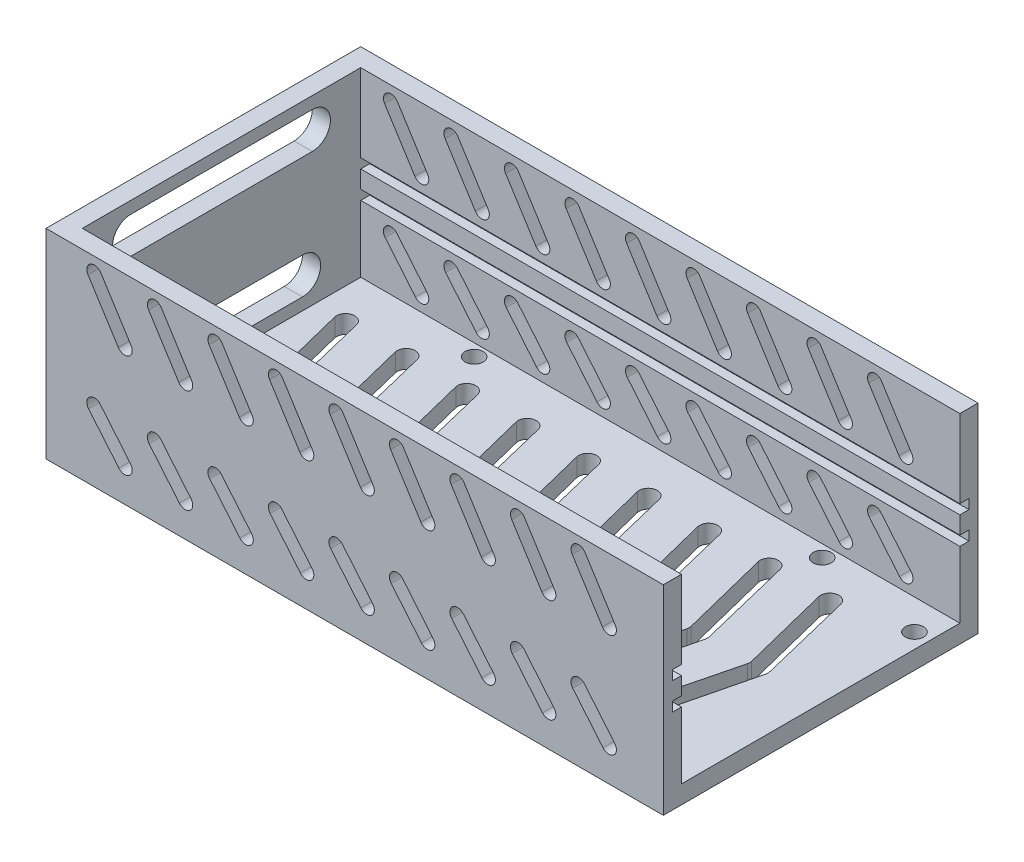
SolidWorks part; units mm, degrees
ref_plane "Front Plane" through (0, 0, 0) normal (0, 0, 1) x (1, 0, 0)
ref_plane "Top Plane" through (0, 0, 0) normal (0, 1, 0) x (1, 0, 0)
ref_plane "Right Plane" through (0, 0, 0) normal (1, 0, 0) x (0, 0, -1)
sketch "Sketch1" plane through (0, 0, 0) normal (0, 1, 0) x (1, 0, 0)
  line L0 (-28.75, 21) -> (28.75, 21) construction
  line L1 (-28.75, 21) -> (-28.75, -21) construction
  line L2 (-25.25, -21) -> (25.25, -21) construction
  line L3 (-49.5, -26) -> (49.5, -26)
  line L4 (-49.5, -26) -> (-49.5, 26)
  line L5 (-49.5, 26) -> (49.5, 26)
  line L6 (49.5, -26) -> (49.5, 26)
  line L7 (-49.5, -26) -> (49.5, 26) construction
  line L8 (-49.5, 26) -> (49.5, -26) construction
  circle A0 centre (28.75, 21) radius 1.5
  circle A1 centre (-28.75, 21) radius 1.5
  circle A2 centre (25.25, -21) radius 1.5
  circle A3 centre (-25.25, -21) radius 1.5
  point P8 (0, 21)
  point P10 (-28.75, 0)
  point P11 (0, 0)
  point P17 (0, -21)
  dimension "D1" = 3
  dimension "D2" = 3
  dimension "D3" = 3
  dimension "D4" = 3
  dimension "D5" = 57.5
  dimension "D6" = 50.5
  dimension "D7" = 42
  dimension "D8" = 42
  dimension "D9" = 52
  dimension "D10" = 99
extrude "Boss-Extrude1" add sketch "Sketch1" along normal blind 33
sketch "Sketch2" plane through (0, 33, 0) normal (0, 1, 0) x (1, 0, 0)
  line L5 (49.5, -26) -> (49.5, 26) construction
  line L6 (-49.5, -23) -> (49.5, -23)
  line L8 (-49.5, -23) -> (-49.5, 23)
  line L9 (-49.5, 23) -> (49.5, 23)
  line L10 (49.5, -23) -> (49.5, 23)
  line L11 (-49.5, -23) -> (49.5, 23) construction
  line L12 (-49.5, 23) -> (49.5, -23) construction
  point P0 (0, 0)
  dimension "D1" = 46
extrude "Cut-Extrude1" cut sketch "Sketch2" against normal blind 30
sketch "Sketch3" plane through (49.5, 0, 0) normal (1, 0, 0) x (0, 0, -1)
  line L0 (-23, 3) -> (-23, 33) construction
  line L1 (-23, 15.6) -> (-24.5, 15.6)
  line L2 (-23, 15.6) -> (-23, 14)
  line L3 (-23, 14) -> (-24.5, 14)
  line L4 (-24.5, 15.6) -> (-24.5, 14)
  line L5 (-23, 3) -> (23, 3) construction
  line L6 (0, 0) -> (0, 22.1348) construction
  line L7 (24.5, 15.6) -> (24.5, 14)
  line L8 (23, 14) -> (24.5, 14)
  line L9 (23, 15.6) -> (23, 14)
  line L10 (23, 15.6) -> (24.5, 15.6)
  line L11 (-23, 18.5) -> (-24.5, 18.5)
  line L12 (-24.5, 20.1) -> (-24.5, 18.5)
  line L13 (-23, 20.1) -> (-23, 18.5)
  line L14 (-23, 20.1) -> (-24.5, 20.1)
  line L15 (23, 20.1) -> (24.5, 20.1)
  line L16 (23, 20.1) -> (23, 18.5)
  line L17 (24.5, 20.1) -> (24.5, 18.5)
  line L18 (23, 18.5) -> (24.5, 18.5)
  point P19 (-23.75, 18.5)
  point P20 (-23.75, 15.6)
  dimension "D1" = 1.5
  dimension "D2" = 1.6
  dimension "D3" = 11
  dimension "D4" = 2.9
  dimension "D5" = 1.5
  dimension "D6" = 1.6
extrude "Cut-Extrude2" cut sketch "Sketch3" against normal up to surface (99 mm away) up to face at (-49.5, 17.25, 0)
sketch "Sketch4" plane through (0, 0, 0) normal (0, 1, 0) x (1, 0, 0)
  line L1 (-49.5, 26) -> (-52.5, 26)
  line L2 (-49.5, 26) -> (-49.5, -26)
  line L3 (-49.5, -26) -> (-52.5, -26)
  line L4 (-52.5, 26) -> (-52.5, -26)
  dimension "D1" = 52
  dimension "D2" = 3
extrude "Boss-Extrude2" add sketch "Sketch4" along normal up to surface (33 mm away) up to face at (0, 33, -24.5)
sketch "Sketch5" plane through (-49.5, 0, 0) normal (1, 0, 0) x (0, 0, -1)
  line L0 (-15, 31) -> (15, 31)
  line L1 (-15, 25) -> (15, 25)
  line L4 (-13.3752, 11) -> (13.3752, 11)
  line L5 (-13.3752, 5) -> (13.3752, 5)
  line L7 (23, 3) -> (-23, 3) construction
  line L8 (23, 33) -> (-23, 33) construction
  arc A0 (15, 25) -> (15, 31) centre (15, 28) ccw
  arc A1 (-15, 31) -> (-15, 25) centre (-15, 28) ccw
  arc A2 (-13.3752, 11) -> (-13.3752, 5) centre (-13.3752, 8) ccw
  arc A3 (13.3752, 5) -> (13.3752, 11) centre (13.3752, 8) ccw
  point P3 (0, 31)
  dimension "D1" = 6
  dimension "D2" = 6
  dimension "D3" = 6
  dimension "D4" = 6
  dimension "D5" = 2
  dimension "D6" = 2
  dimension "D7" = 30
extrude "Cut-Extrude3" cut sketch "Sketch5" against normal up to surface (3 mm away) up to face at (-52.5, 16.5, 0)
sketch "Sketch6" plane through (0, 0, -23) normal (0, 0, 1) x (1, 0, 0)
  line L0 (-45.5562, 29.8315) -> (-40.5562, 21.9315)
  line L1 (-44.5, 30.5) -> (-39.5, 22.6) construction
  line L2 (-43.4438, 31.1685) -> (-38.4438, 23.2685)
  line L3 (49.5, 33) -> (-49.5, 33) construction
  line L4 (-49.5, 20.1) -> (49.5, 20.1) construction
  line L5 (-49.5, 20.1) -> (-49.5, 33) construction
  line L6 (-43.5397, 12.3002) -> (-38.5397, 6.3002)
  line L7 (-44.5, 11.5) -> (-39.5, 5.5) construction
  line L8 (-45.4603, 10.6998) -> (-40.4603, 4.6998)
  line L9 (-49.5, 3) -> (-49.5, 14) construction
  line L10 (-49.5, 14) -> (49.5, 14) construction
  line L11 (49.5, 3) -> (-49.5, 3) construction
  line L12 (-35.5562, 29.8315) -> (-30.5562, 21.9315)
  line L13 (-33.4438, 31.1685) -> (-28.4438, 23.2685)
  line L14 (-33.5397, 12.3002) -> (-28.5397, 6.3002)
  line L15 (-35.4603, 10.6998) -> (-30.4603, 4.6998)
  line L16 (-34.5, 30.5) -> (-29.5, 22.6) construction
  line L17 (-34.5, 11.5) -> (-29.5, 5.5) construction
  line L18 (-25.5562, 29.8315) -> (-20.5562, 21.9315)
  line L19 (-23.4438, 31.1685) -> (-18.4438, 23.2685)
  line L20 (-23.5397, 12.3002) -> (-18.5397, 6.3002)
  line L21 (-25.4603, 10.6998) -> (-20.4603, 4.6998)
  line L22 (-24.5, 30.5) -> (-19.5, 22.6) construction
  line L23 (-24.5, 11.5) -> (-19.5, 5.5) construction
  line L24 (-15.5562, 29.8315) -> (-10.5562, 21.9315)
  line L25 (-13.4438, 31.1685) -> (-8.4438, 23.2685)
  line L26 (-13.5397, 12.3002) -> (-8.5397, 6.3002)
  line L27 (-15.4603, 10.6998) -> (-10.4603, 4.6998)
  line L28 (-14.5, 30.5) -> (-9.5, 22.6) construction
  line L29 (-14.5, 11.5) -> (-9.5, 5.5) construction
  line L30 (-5.5562, 29.8315) -> (-0.5562, 21.9315)
  line L31 (-3.4438, 31.1685) -> (1.5562, 23.2685)
  line L32 (-3.5397, 12.3002) -> (1.4603, 6.3002)
  line L33 (-5.4603, 10.6998) -> (-0.4603, 4.6998)
  line L34 (-4.5, 30.5) -> (0.5, 22.6) construction
  line L35 (-4.5, 11.5) -> (0.5, 5.5) construction
  line L36 (4.4438, 29.8315) -> (9.4438, 21.9315)
  line L37 (6.5562, 31.1685) -> (11.5562, 23.2685)
  line L38 (6.4603, 12.3002) -> (11.4603, 6.3002)
  line L39 (4.5397, 10.6998) -> (9.5397, 4.6998)
  line L40 (5.5, 30.5) -> (10.5, 22.6) construction
  line L41 (5.5, 11.5) -> (10.5, 5.5) construction
  line L42 (14.4438, 29.8315) -> (19.4438, 21.9315)
  line L43 (16.5562, 31.1685) -> (21.5562, 23.2685)
  line L44 (16.4603, 12.3002) -> (21.4603, 6.3002)
  line L45 (14.5397, 10.6998) -> (19.5397, 4.6998)
  line L46 (15.5, 30.5) -> (20.5, 22.6) construction
  line L47 (15.5, 11.5) -> (20.5, 5.5) construction
  line L48 (24.4438, 29.8315) -> (29.4438, 21.9315)
  line L49 (26.5562, 31.1685) -> (31.5562, 23.2685)
  line L50 (26.4603, 12.3002) -> (31.4603, 6.3002)
  line L51 (24.5397, 10.6998) -> (29.5397, 4.6998)
  line L52 (25.5, 30.5) -> (30.5, 22.6) construction
  line L53 (25.5, 11.5) -> (30.5, 5.5) construction
  line L54 (34.4438, 29.8315) -> (39.4438, 21.9315)
  line L55 (36.5562, 31.1685) -> (41.5562, 23.2685)
  line L56 (36.4603, 12.3002) -> (41.4603, 6.3002)
  line L57 (34.5397, 10.6998) -> (39.5397, 4.6998)
  line L58 (35.5, 30.5) -> (40.5, 22.6) construction
  line L59 (35.5, 11.5) -> (40.5, 5.5) construction
  arc A0 (-43.4438, 31.1685) -> (-45.5562, 29.8315) centre (-44.5, 30.5) ccw
  arc A1 (-40.5562, 21.9315) -> (-38.4438, 23.2685) centre (-39.5, 22.6) ccw
  arc A2 (-40.4603, 4.6998) -> (-38.5397, 6.3002) centre (-39.5, 5.5) ccw
  arc A3 (-43.5397, 12.3002) -> (-45.4603, 10.6998) centre (-44.5, 11.5) ccw
  arc A4 (-33.4438, 31.1685) -> (-35.5562, 29.8315) centre (-34.5, 30.5) ccw
  arc A5 (-30.5562, 21.9315) -> (-28.4438, 23.2685) centre (-29.5, 22.6) ccw
  arc A6 (-30.4603, 4.6998) -> (-28.5397, 6.3002) centre (-29.5, 5.5) ccw
  arc A7 (-33.5397, 12.3002) -> (-35.4603, 10.6998) centre (-34.5, 11.5) ccw
  arc A8 (-23.4438, 31.1685) -> (-25.5562, 29.8315) centre (-24.5, 30.5) ccw
  arc A9 (-20.5562, 21.9315) -> (-18.4438, 23.2685) centre (-19.5, 22.6) ccw
  arc A10 (-20.4603, 4.6998) -> (-18.5397, 6.3002) centre (-19.5, 5.5) ccw
  arc A11 (-23.5397, 12.3002) -> (-25.4603, 10.6998) centre (-24.5, 11.5) ccw
  arc A12 (-13.4438, 31.1685) -> (-15.5562, 29.8315) centre (-14.5, 30.5) ccw
  arc A13 (-10.5562, 21.9315) -> (-8.4438, 23.2685) centre (-9.5, 22.6) ccw
  arc A14 (-10.4603, 4.6998) -> (-8.5397, 6.3002) centre (-9.5, 5.5) ccw
  arc A15 (-13.5397, 12.3002) -> (-15.4603, 10.6998) centre (-14.5, 11.5) ccw
  arc A16 (-3.4438, 31.1685) -> (-5.5562, 29.8315) centre (-4.5, 30.5) ccw
  arc A17 (-0.5562, 21.9315) -> (1.5562, 23.2685) centre (0.5, 22.6) ccw
  arc A18 (-0.4603, 4.6998) -> (1.4603, 6.3002) centre (0.5, 5.5) ccw
  arc A19 (-3.5397, 12.3002) -> (-5.4603, 10.6998) centre (-4.5, 11.5) ccw
  arc A20 (6.5562, 31.1685) -> (4.4438, 29.8315) centre (5.5, 30.5) ccw
  arc A21 (9.4438, 21.9315) -> (11.5562, 23.2685) centre (10.5, 22.6) ccw
  arc A22 (9.5397, 4.6998) -> (11.4603, 6.3002) centre (10.5, 5.5) ccw
  arc A23 (6.4603, 12.3002) -> (4.5397, 10.6998) centre (5.5, 11.5) ccw
  arc A24 (16.5562, 31.1685) -> (14.4438, 29.8315) centre (15.5, 30.5) ccw
  arc A25 (19.4438, 21.9315) -> (21.5562, 23.2685) centre (20.5, 22.6) ccw
  arc A26 (19.5397, 4.6998) -> (21.4603, 6.3002) centre (20.5, 5.5) ccw
  arc A27 (16.4603, 12.3002) -> (14.5397, 10.6998) centre (15.5, 11.5) ccw
  arc A28 (26.5562, 31.1685) -> (24.4438, 29.8315) centre (25.5, 30.5) ccw
  arc A29 (29.4438, 21.9315) -> (31.5562, 23.2685) centre (30.5, 22.6) ccw
  arc A30 (29.5397, 4.6998) -> (31.4603, 6.3002) centre (30.5, 5.5) ccw
  arc A31 (26.4603, 12.3002) -> (24.5397, 10.6998) centre (25.5, 11.5) ccw
  arc A32 (36.5562, 31.1685) -> (34.4438, 29.8315) centre (35.5, 30.5) ccw
  arc A33 (39.4438, 21.9315) -> (41.5562, 23.2685) centre (40.5, 22.6) ccw
  arc A34 (39.5397, 4.6998) -> (41.4603, 6.3002) centre (40.5, 5.5) ccw
  arc A35 (36.4603, 12.3002) -> (34.5397, 10.6998) centre (35.5, 11.5) ccw
  dimension "D1" = 2.5
  dimension "D2" = 2.5
  dimension "D7" = 2.5
  dimension "D8" = 2.5
  dimension "D3" = 2.5
  dimension "D4" = 2.5
  dimension "D5" = 5
  dimension "D6" = 5
  dimension "D9" = 5
  dimension "D10" = 5
  dimension "D11" = 2.5
  dimension "D12" = 2.5
  dimension "D13" = 9
extrude "Cut-Extrude4" cut sketch "Sketch6" against normal up to surface (3 mm away) up to face at (-1.5, 16.5, -26)
sketch "Sketch7" plane through (0, 0, -26) normal (0, 0, -1) x (-1, 0, 0)
  line L0 (40.5562, 21.9315) -> (45.5562, 29.8315)
  line L1 (43.4438, 31.1685) -> (38.4438, 23.2685)
  line L2 (43.5397, 12.3002) -> (38.5397, 6.3002)
  line L3 (40.4603, 4.6998) -> (45.4603, 10.6998)
  line L4 (30.5562, 21.9315) -> (35.5562, 29.8315)
  line L5 (33.4438, 31.1685) -> (28.4438, 23.2685)
  line L6 (33.5397, 12.3002) -> (28.5397, 6.3002)
  line L7 (30.4603, 4.6998) -> (35.4603, 10.6998)
  line L8 (20.5562, 21.9315) -> (25.5562, 29.8315)
  line L9 (23.4438, 31.1685) -> (18.4438, 23.2685)
  line L10 (23.5397, 12.3002) -> (18.5397, 6.3002)
  line L11 (20.4603, 4.6998) -> (25.4603, 10.6998)
  line L12 (10.5562, 21.9315) -> (15.5562, 29.8315)
  line L13 (13.4438, 31.1685) -> (8.4438, 23.2685)
  line L14 (13.5397, 12.3002) -> (8.5397, 6.3002)
  line L15 (10.4603, 4.6998) -> (15.4603, 10.6998)
  line L16 (0.5562, 21.9315) -> (5.5562, 29.8315)
  line L17 (3.4438, 31.1685) -> (-1.5562, 23.2685)
  line L18 (3.5397, 12.3002) -> (-1.4603, 6.3002)
  line L19 (0.4603, 4.6998) -> (5.4603, 10.6998)
  line L20 (-9.4438, 21.9315) -> (-4.4438, 29.8315)
  line L21 (-6.5562, 31.1685) -> (-11.5562, 23.2685)
  line L22 (-6.4603, 12.3002) -> (-11.4603, 6.3002)
  line L23 (-9.5397, 4.6998) -> (-4.5397, 10.6998)
  line L24 (-19.4438, 21.9315) -> (-14.4438, 29.8315)
  line L25 (-16.5562, 31.1685) -> (-21.5562, 23.2685)
  line L26 (-16.4603, 12.3002) -> (-21.4603, 6.3002)
  line L27 (-19.5397, 4.6998) -> (-14.5397, 10.6998)
  line L28 (-29.4438, 21.9315) -> (-24.4438, 29.8315)
  line L29 (-26.5562, 31.1685) -> (-31.5562, 23.2685)
  line L30 (-26.4603, 12.3002) -> (-31.4603, 6.3002)
  line L31 (-29.5397, 4.6998) -> (-24.5397, 10.6998)
  line L32 (-39.4438, 21.9315) -> (-34.4438, 29.8315)
  line L33 (-36.5562, 31.1685) -> (-41.5562, 23.2685)
  line L34 (-36.4603, 12.3002) -> (-41.4603, 6.3002)
  line L35 (-39.5397, 4.6998) -> (-34.5397, 10.6998)
  arc A0 (45.5562, 29.8315) -> (43.4438, 31.1685) centre (44.5, 30.5) ccw
  arc A1 (38.4438, 23.2685) -> (40.5562, 21.9315) centre (39.5, 22.6) ccw
  arc A2 (38.5397, 6.3002) -> (40.4603, 4.6998) centre (39.5, 5.5) ccw
  arc A3 (45.4603, 10.6998) -> (43.5397, 12.3002) centre (44.5, 11.5) ccw
  arc A4 (45.4603, 10.6998) -> (43.5397, 12.3002) centre (44.5, 11.5) ccw construction
  arc A5 (38.5397, 6.3002) -> (40.4603, 4.6998) centre (39.5, 5.5) ccw construction
  arc A6 (35.5562, 29.8315) -> (33.4438, 31.1685) centre (34.5, 30.5) ccw
  arc A7 (28.4438, 23.2685) -> (30.5562, 21.9315) centre (29.5, 22.6) ccw
  arc A8 (28.5397, 6.3002) -> (30.4603, 4.6998) centre (29.5, 5.5) ccw
  arc A9 (35.4603, 10.6998) -> (33.5397, 12.3002) centre (34.5, 11.5) ccw
  arc A10 (25.5562, 29.8315) -> (23.4438, 31.1685) centre (24.5, 30.5) ccw
  arc A11 (18.4438, 23.2685) -> (20.5562, 21.9315) centre (19.5, 22.6) ccw
  arc A12 (18.5397, 6.3002) -> (20.4603, 4.6998) centre (19.5, 5.5) ccw
  arc A13 (25.4603, 10.6998) -> (23.5397, 12.3002) centre (24.5, 11.5) ccw
  arc A14 (15.5562, 29.8315) -> (13.4438, 31.1685) centre (14.5, 30.5) ccw
  arc A15 (8.4438, 23.2685) -> (10.5562, 21.9315) centre (9.5, 22.6) ccw
  arc A16 (8.5397, 6.3002) -> (10.4603, 4.6998) centre (9.5, 5.5) ccw
  arc A17 (15.4603, 10.6998) -> (13.5397, 12.3002) centre (14.5, 11.5) ccw
  arc A18 (5.5562, 29.8315) -> (3.4438, 31.1685) centre (4.5, 30.5) ccw
  arc A19 (-1.5562, 23.2685) -> (0.5562, 21.9315) centre (-0.5, 22.6) ccw
  arc A20 (-1.4603, 6.3002) -> (0.4603, 4.6998) centre (-0.5, 5.5) ccw
  arc A21 (5.4603, 10.6998) -> (3.5397, 12.3002) centre (4.5, 11.5) ccw
  arc A22 (-4.4438, 29.8315) -> (-6.5562, 31.1685) centre (-5.5, 30.5) ccw
  arc A23 (-11.5562, 23.2685) -> (-9.4438, 21.9315) centre (-10.5, 22.6) ccw
  arc A24 (-11.4603, 6.3002) -> (-9.5397, 4.6998) centre (-10.5, 5.5) ccw
  arc A25 (-4.5397, 10.6998) -> (-6.4603, 12.3002) centre (-5.5, 11.5) ccw
  arc A26 (-14.4438, 29.8315) -> (-16.5562, 31.1685) centre (-15.5, 30.5) ccw
  arc A27 (-21.5562, 23.2685) -> (-19.4438, 21.9315) centre (-20.5, 22.6) ccw
  arc A28 (-21.4603, 6.3002) -> (-19.5397, 4.6998) centre (-20.5, 5.5) ccw
  arc A29 (-14.5397, 10.6998) -> (-16.4603, 12.3002) centre (-15.5, 11.5) ccw
  arc A30 (-24.4438, 29.8315) -> (-26.5562, 31.1685) centre (-25.5, 30.5) ccw
  arc A31 (-31.5562, 23.2685) -> (-29.4438, 21.9315) centre (-30.5, 22.6) ccw
  arc A32 (-31.4603, 6.3002) -> (-29.5397, 4.6998) centre (-30.5, 5.5) ccw
  arc A33 (-24.5397, 10.6998) -> (-26.4603, 12.3002) centre (-25.5, 11.5) ccw
  arc A34 (-34.4438, 29.8315) -> (-36.5562, 31.1685) centre (-35.5, 30.5) ccw
  arc A35 (-41.5562, 23.2685) -> (-39.4438, 21.9315) centre (-40.5, 22.6) ccw
  arc A36 (-41.4603, 6.3002) -> (-39.5397, 4.6998) centre (-40.5, 5.5) ccw
  arc A37 (-34.5397, 10.6998) -> (-36.4603, 12.3002) centre (-35.5, 11.5) ccw
  dimension "D1" = 9
extrude "Cut-Extrude5" cut sketch "Sketch7" against normal up to surface (52 mm away) up to face at (-1.5, 16.5, 26)
sketch "Sketch8" plane through (0, 3, 0) normal (0, 1, 0) x (1, 0, 0)
  line L0 (-49.5, 23) -> (-49.5, -23) construction
  line L1 (-49.5, -23) -> (49.5, -23) construction
  line L2 (-42.2578, 0.3558) -> (-45.9679, 15.1913)
  line L3 (49.5, 23) -> (-49.5, 23) construction
  line L4 (-43.0428, 15.8558) -> (-39.2578, 0.3558)
  line L5 (-39.2578, -0.3558) -> (-43.0428, -15.8558)
  line L6 (-45.9668, -15.1862) -> (-42.2578, -0.3558)
  line L7 (-32.2578, 0.3558) -> (-35.9679, 15.1913)
  line L8 (-33.0428, 15.8558) -> (-29.2578, 0.3558)
  line L9 (-29.2578, -0.3558) -> (-33.0428, -15.8558)
  line L10 (-35.9668, -15.1862) -> (-32.2578, -0.3558)
  line L11 (-22.2578, 0.3558) -> (-25.9679, 15.1913)
  line L12 (-23.0428, 15.8558) -> (-19.2578, 0.3558)
  line L13 (-19.2578, -0.3558) -> (-23.0428, -15.8558)
  line L14 (-25.9668, -15.1862) -> (-22.2578, -0.3558)
  line L15 (-12.2578, 0.3558) -> (-15.9679, 15.1913)
  line L16 (-13.0428, 15.8558) -> (-9.2578, 0.3558)
  line L17 (-9.2578, -0.3558) -> (-13.0428, -15.8558)
  line L18 (-15.9668, -15.1862) -> (-12.2578, -0.3558)
  line L19 (-2.2578, 0.3558) -> (-5.9679, 15.1913)
  line L20 (-3.0428, 15.8558) -> (0.7422, 0.3558)
  line L21 (0.7422, -0.3558) -> (-3.0428, -15.8558)
  line L22 (-5.9668, -15.1862) -> (-2.2578, -0.3558)
  line L23 (7.7422, 0.3558) -> (4.0321, 15.1913)
  line L24 (6.9572, 15.8558) -> (10.7422, 0.3558)
  line L25 (10.7422, -0.3558) -> (6.9572, -15.8558)
  line L26 (4.0332, -15.1862) -> (7.7422, -0.3558)
  line L27 (17.7422, 0.3558) -> (14.0321, 15.1913)
  line L28 (16.9572, 15.8558) -> (20.7422, 0.3558)
  line L29 (20.7422, -0.3558) -> (16.9572, -15.8558)
  line L30 (14.0332, -15.1862) -> (17.7422, -0.3558)
  line L31 (27.7422, 0.3558) -> (24.0321, 15.1913)
  line L32 (26.9572, 15.8558) -> (30.7422, 0.3558)
  line L33 (30.7422, -0.3558) -> (26.9572, -15.8558)
  line L34 (24.0332, -15.1862) -> (27.7422, -0.3558)
  line L35 (37.7422, 0.3558) -> (34.0321, 15.1913)
  line L36 (36.9572, 15.8558) -> (40.7422, 0.3558)
  line L37 (40.7422, -0.3558) -> (36.9572, -15.8558)
  line L38 (34.0332, -15.1862) -> (37.7422, -0.3558)
  arc A0 (-43.0428, 15.8558) -> (-45.9679, 15.1913) centre (-44.5, 15.5) ccw
  arc A1 (-39.2578, -0.3558) -> (-39.2578, 0.3558) centre (-40.715, 0) ccw
  arc A2 (-45.9668, -15.1862) -> (-43.0428, -15.8558) centre (-44.5, -15.5) ccw
  arc A4 (-42.2578, -0.3558) -> (-42.2578, 0.3558) centre (-43.715, 0) ccw
  arc A5 (-33.0428, 15.8558) -> (-35.9679, 15.1913) centre (-34.5, 15.5) ccw
  arc A6 (-29.2578, -0.3558) -> (-29.2578, 0.3558) centre (-30.715, 0) ccw
  arc A7 (-35.9668, -15.1862) -> (-33.0428, -15.8558) centre (-34.5, -15.5) ccw
  arc A8 (-32.2578, -0.3558) -> (-32.2578, 0.3558) centre (-33.715, 0) ccw
  arc A9 (-23.0428, 15.8558) -> (-25.9679, 15.1913) centre (-24.5, 15.5) ccw
  arc A10 (-19.2578, -0.3558) -> (-19.2578, 0.3558) centre (-20.715, 0) ccw
  arc A11 (-25.9668, -15.1862) -> (-23.0428, -15.8558) centre (-24.5, -15.5) ccw
  arc A12 (-22.2578, -0.3558) -> (-22.2578, 0.3558) centre (-23.715, 0) ccw
  arc A13 (-13.0428, 15.8558) -> (-15.9679, 15.1913) centre (-14.5, 15.5) ccw
  arc A14 (-9.2578, -0.3558) -> (-9.2578, 0.3558) centre (-10.715, 0) ccw
  arc A15 (-15.9668, -15.1862) -> (-13.0428, -15.8558) centre (-14.5, -15.5) ccw
  arc A16 (-12.2578, -0.3558) -> (-12.2578, 0.3558) centre (-13.715, 0) ccw
  arc A17 (-3.0428, 15.8558) -> (-5.9679, 15.1913) centre (-4.5, 15.5) ccw
  arc A18 (0.7422, -0.3558) -> (0.7422, 0.3558) centre (-0.715, 0) ccw
  arc A19 (-5.9668, -15.1862) -> (-3.0428, -15.8558) centre (-4.5, -15.5) ccw
  arc A20 (-2.2578, -0.3558) -> (-2.2578, 0.3558) centre (-3.715, 0) ccw
  arc A21 (6.9572, 15.8558) -> (4.0321, 15.1913) centre (5.5, 15.5) ccw
  arc A22 (10.7422, -0.3558) -> (10.7422, 0.3558) centre (9.285, 0) ccw
  arc A23 (4.0332, -15.1862) -> (6.9572, -15.8558) centre (5.5, -15.5) ccw
  arc A24 (7.7422, -0.3558) -> (7.7422, 0.3558) centre (6.285, 0) ccw
  arc A25 (16.9572, 15.8558) -> (14.0321, 15.1913) centre (15.5, 15.5) ccw
  arc A26 (20.7422, -0.3558) -> (20.7422, 0.3558) centre (19.285, 0) ccw
  arc A27 (14.0332, -15.1862) -> (16.9572, -15.8558) centre (15.5, -15.5) ccw
  arc A28 (17.7422, -0.3558) -> (17.7422, 0.3558) centre (16.285, 0) ccw
  arc A29 (26.9572, 15.8558) -> (24.0321, 15.1913) centre (25.5, 15.5) ccw
  arc A30 (30.7422, -0.3558) -> (30.7422, 0.3558) centre (29.285, 0) ccw
  arc A31 (24.0332, -15.1862) -> (26.9572, -15.8558) centre (25.5, -15.5) ccw
  arc A32 (27.7422, -0.3558) -> (27.7422, 0.3558) centre (26.285, 0) ccw
  arc A33 (36.9572, 15.8558) -> (34.0321, 15.1913) centre (35.5, 15.5) ccw
  arc A34 (40.7422, -0.3558) -> (40.7422, 0.3558) centre (39.285, 0) ccw
  arc A35 (34.0332, -15.1862) -> (36.9572, -15.8558) centre (35.5, -15.5) ccw
  arc A36 (37.7422, -0.3558) -> (37.7422, 0.3558) centre (36.285, 0) ccw
  dimension "D1" = 3
  dimension "D2" = 3
  dimension "D3" = 3
  dimension "D4" = 5
  dimension "D5" = 7.5
  dimension "D6" = 7.5
  dimension "D7" = 15.5
  dimension "D8" = 9
extrude "Cut-Extrude6" cut sketch "Sketch8" against normal up to surface (3 mm away) up to face at (25.25, 0, 22.5)
sketch "Sketch10" plane through (0, 3, 0) normal (0, 1, 0) x (1, 0, 0)
  line L0 (49.5, 23) -> (-49.5, 23) construction
  line L1 (49.5, -23) -> (49.5, 23) construction
  circle A0 centre (47, 18) radius 1.5
  dimension "D1" = 3
  dimension "D2" = 5
  dimension "D3" = 2.5
extrude "Cut-Extrude7" cut sketch "Sketch10" against normal up to surface (3 mm away) up to face at (-42.7029, 0, -0.0004)
